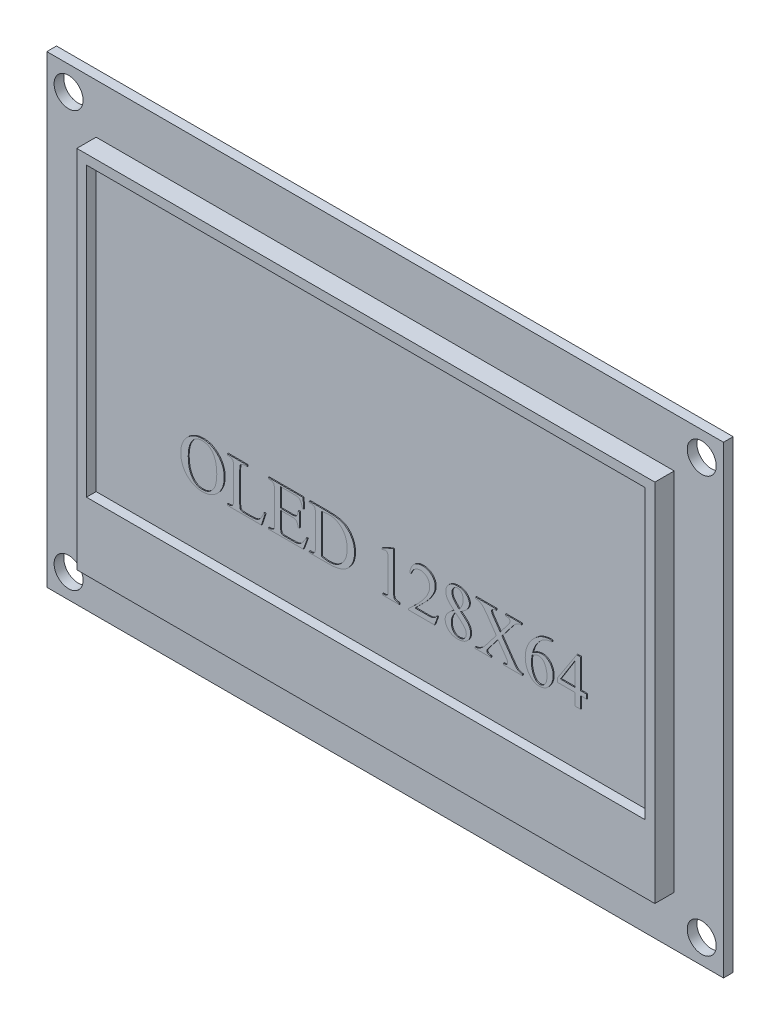
SolidWorks part; units mm, degrees
ref_plane "前视基准面" through (0, 0, 0) normal (0, 0, 1) x (1, 0, 0)
ref_plane "上视基准面" through (0, 0, 0) normal (0, 1, 0) x (1, 0, 0)
ref_plane "右视基准面" through (0, 0, 0) normal (1, 0, 0) x (0, 0, -1)
other "Configuration Table"
sketch "草图1" plane through (0, 0, 0) normal (0, 0, 1) x (1, 0, 0)
  line L1 (-35, -24) -> (35, -24)
  line L2 (-35, -24) -> (-35, 24)
  line L3 (-35, 24) -> (35, 24)
  line L4 (35, -24) -> (35, 24)
  line L5 (-35, -24) -> (35, 24) construction
  line L6 (-35, 24) -> (35, -24) construction
  circle A0 centre (32.75, -21.5) radius 1.5
  circle A1 centre (-32.75, -21.5) radius 1.5
  circle A2 centre (-32.75, 21.5) radius 1.5
  circle A3 centre (32.75, 21.5) radius 1.5
  point P0 (0, 0)
  dimension "D3" = 3
  dimension "D4" = 21.5
  dimension "D5" = 32.75
  dimension "D1" = 70
  dimension "D2" = 48
  dimension "D6" = 2
  dimension "D7" = 2
extrude "凸台-拉伸1" add sketch "草图1" along normal blind 1
sketch "草图2" plane through (0, 0, 1) normal (0, 0, 1) x (1, 0, 0)
  line L1 (-29.9, -18.88) -> (29.9, -18.88)
  line L2 (-29.9, -18.88) -> (-29.9, 18.88)
  line L3 (-29.9, 18.88) -> (29.9, 18.88)
  line L4 (29.9, -18.88) -> (29.9, 18.88)
  line L5 (-29.9, -18.88) -> (29.9, 18.88) construction
  line L6 (-29.9, 18.88) -> (29.9, -18.88) construction
  point P0 (0, 0)
  dimension "D1" = 59.8
  dimension "D2" = 37.76
extrude "凸台-拉伸2" add sketch "草图2" along normal blind 2
sketch "草图3" plane through (0, 0, 3) normal (0, 0, 1) x (1, 0, 0)
  line L1 (-28.9, -11.8743) -> (28.9, -11.8743)
  line L2 (-28.9, -11.8743) -> (-28.9, 17.8857)
  line L3 (-28.9, 17.8857) -> (28.9, 17.8857)
  line L4 (28.9, -11.8743) -> (28.9, 17.8857)
  line L5 (-28.9, -11.8743) -> (28.9, 17.8857) construction
  line L6 (-28.9, 17.8857) -> (28.9, -11.8743) construction
  point P0 (0, 3.0057)
  point P5 (0, 0)
  point P7 (0, 3.0057)
  dimension "D1" = 57.8
  dimension "D2" = 29.76
extrude "切除-拉伸1" cut sketch "草图3" against normal blind 1
sketch "草图4" plane through (0, 0, 2) normal (0, 0, 1) x (1, 0, 0)
  line L0 (-21.3087, -6.2181) -> (23.2749, -6.2181) construction
  text T0 "OLED 128X64" font "Times New Roman" height in points 18
extrude "凸台-拉伸3" add sketch "草图4" along normal blind 0.1
